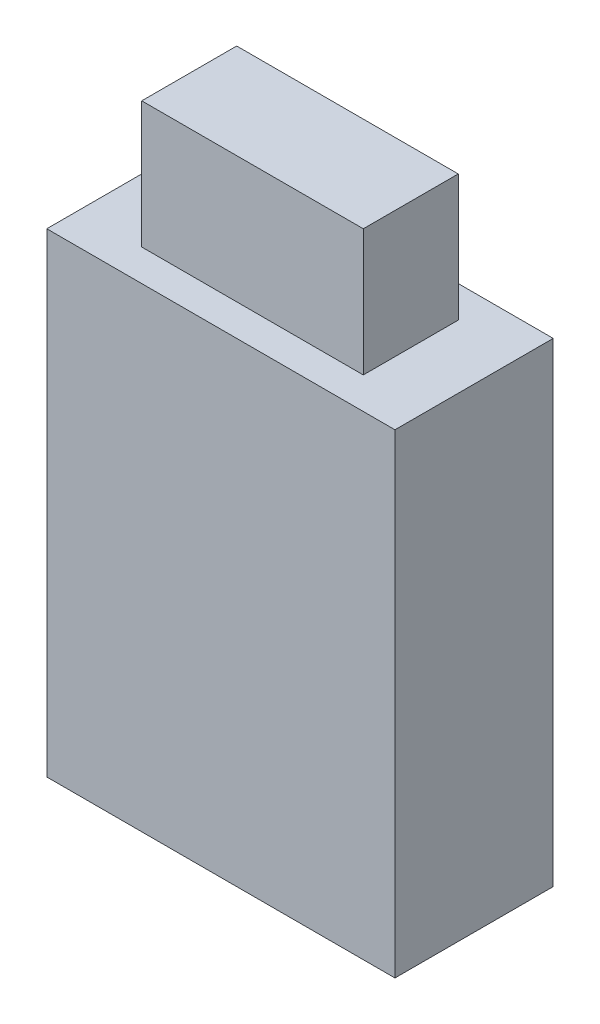
SolidWorks part; units mm, degrees
ref_plane "Front Plane" through (0, 0, 0) normal (0, 0, 1) x (1, 0, 0)
ref_plane "Top Plane" through (0, 0, 0) normal (0, 1, 0) x (1, 0, 0)
ref_plane "Right Plane" through (0, 0, 0) normal (1, 0, 0) x (0, 0, -1)
sketch "Sketch1" plane through (0, 0, 0) normal (0, 0, 1) x (1, 0, 0)
  line L1 (-52, 158) -> (-30, 158)
  line L2 (-52, 158) -> (-52, 188)
  line L3 (-52, 188) -> (-30, 188)
  line L4 (-30, 158) -> (-30, 188)
extrude "Boss-Extrude1" add sketch "Sketch1" along normal blind 10 from offset 56
sketch "Sketch2" plane through (0, 0, 0) normal (0, 0, 1) x (1, 0, 0)
  line L1 (-48, 188) -> (-34, 188)
  line L2 (-48, 188) -> (-48, 196)
  line L3 (-48, 196) -> (-34, 196)
  line L4 (-34, 188) -> (-34, 196)
extrude "Boss-Extrude2" add sketch "Sketch2" along normal blind 6 from offset 58
